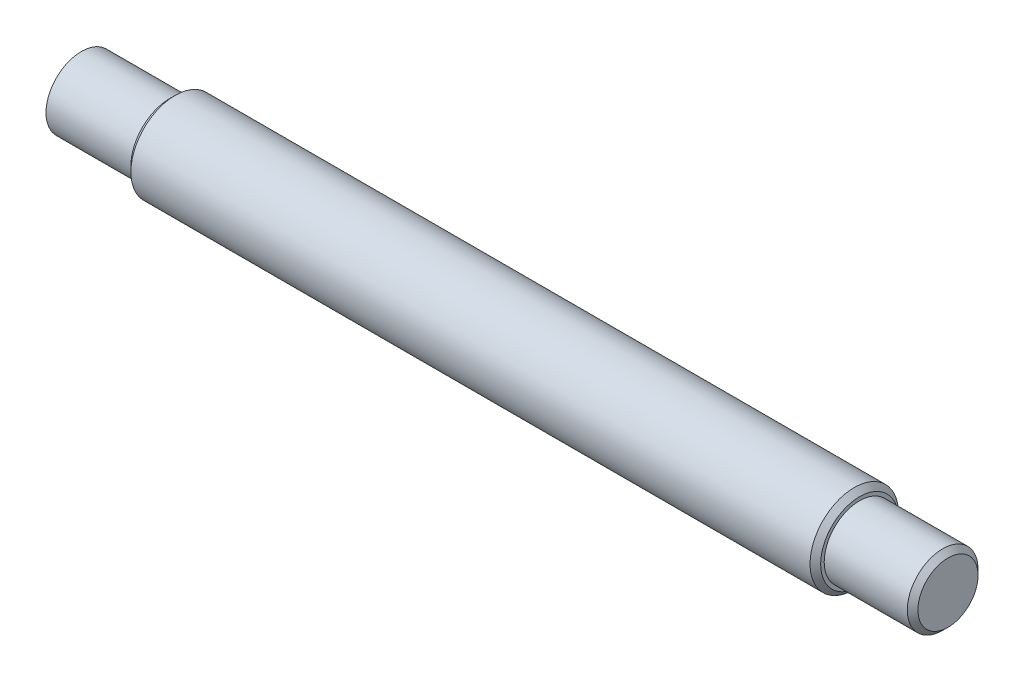
SolidWorks part; units mm, degrees
material "AISI 316 Barre d'acier inoxydable recuit (SS)"
ref_plane "Plan de face" through (0, 0, 0) normal (0, 0, 1) x (1, 0, 0)
ref_plane "Plan de dessus" through (0, 0, 0) normal (0, 1, 0) x (1, 0, 0)
ref_plane "Plan de droite" through (0, 0, 0) normal (1, 0, 0) x (0, 0, -1)
sketch "Esquisse1" plane through (0, 0, 0) normal (0, 0, 1) x (1, 0, 0)
  line L0 (-77.894, 0) -> (89.6314, 0) construction
  line L1 (36, 0) -> (36, 2)
  line L2 (31, 2.5) -> (-8, 2.5)
  line L3 (-8, 2.5) -> (-8, 2)
  line L4 (31, 2.5) -> (31, 2)
  line L5 (31, 2) -> (36, 2)
  line L6 (-8, 2) -> (-13, 2)
  line L7 (-13, 2) -> (-13, 1.2)
  line L8 (-13, 1.2) -> (0, 1.2)
  line L9 (0, 1.2) -> (0, 0)
  line L10 (0, 0) -> (36, 0)
  dimension "D1" = 44
  dimension "D2" = 49
  dimension "D3" = 2.5
  dimension "D4" = 5
  dimension "D5" = 1.2
  dimension "D6" = 13
  dimension "D7" = 2
revolve "Révolution1" add sketch "Esquisse1" angle 360 about L0
chamfer "Chanfrein1" distance 0.3 angle 45 3 edges at (36, 0, 2) (-8, 0, 2.5) (31, 0, 2.5)
